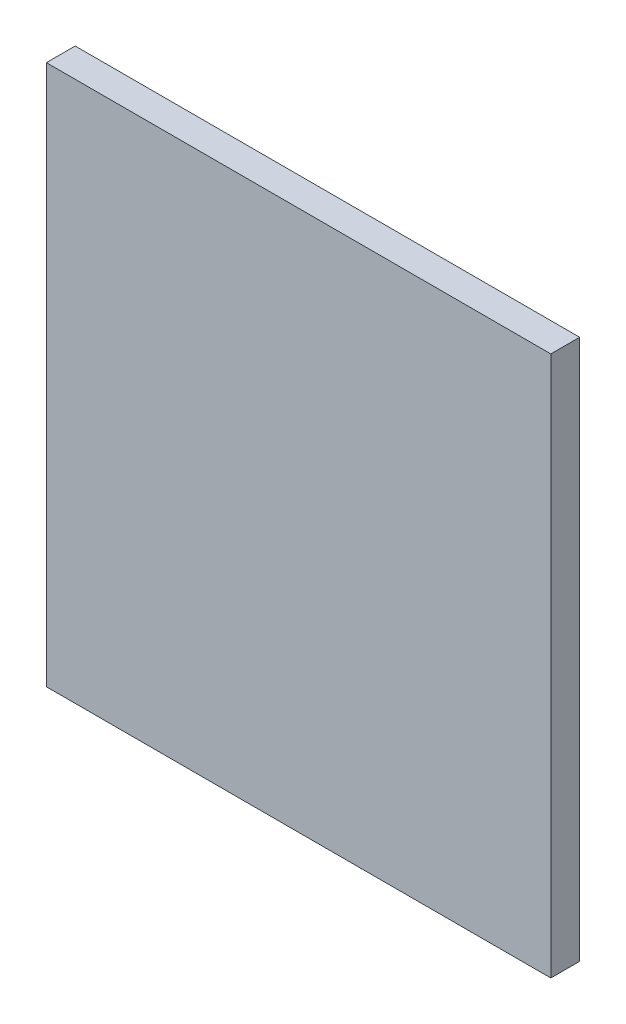
SolidWorks part; units mm, degrees
ref_plane "Front Plane" through (0, 0, 0) normal (0, 0, 1) x (1, 0, 0)
ref_plane "Top Plane" through (0, 0, 0) normal (0, 1, 0) x (1, 0, 0)
ref_plane "Right Plane" through (0, 0, 0) normal (1, 0, 0) x (0, 0, -1)
sketch "Sketch1" plane through (0, 0, 0) normal (0, 0, 1) x (1, 0, 0)
  line L1 (0, 0) -> (70, 0)
  line L2 (0, 0) -> (0, 75)
  line L3 (0, 75) -> (70, 75)
  line L4 (70, 0) -> (70, 75)
  dimension "D1" = 70
  dimension "D2" = 75
extrude "Profile" add sketch "Sketch1" along normal blind 4
equation "\"Profile_Depth\"= 4mm"
equation "\"D1@Profile\" = \"Profile_Depth\""
equation "\"Profile_Sketch_1\"= 70mm"
equation "\"D1@Sketch1\" = \"Profile_Sketch_1\""
equation "\"Profile_Sketch_2\"= 75mm"
equation "\"D2@Sketch1\" = \"Profile_Sketch_2\""
equation "\"EnvelopeWidth\"= 70mm"
equation "\"EnvelopeHeight\"= 75mm"
